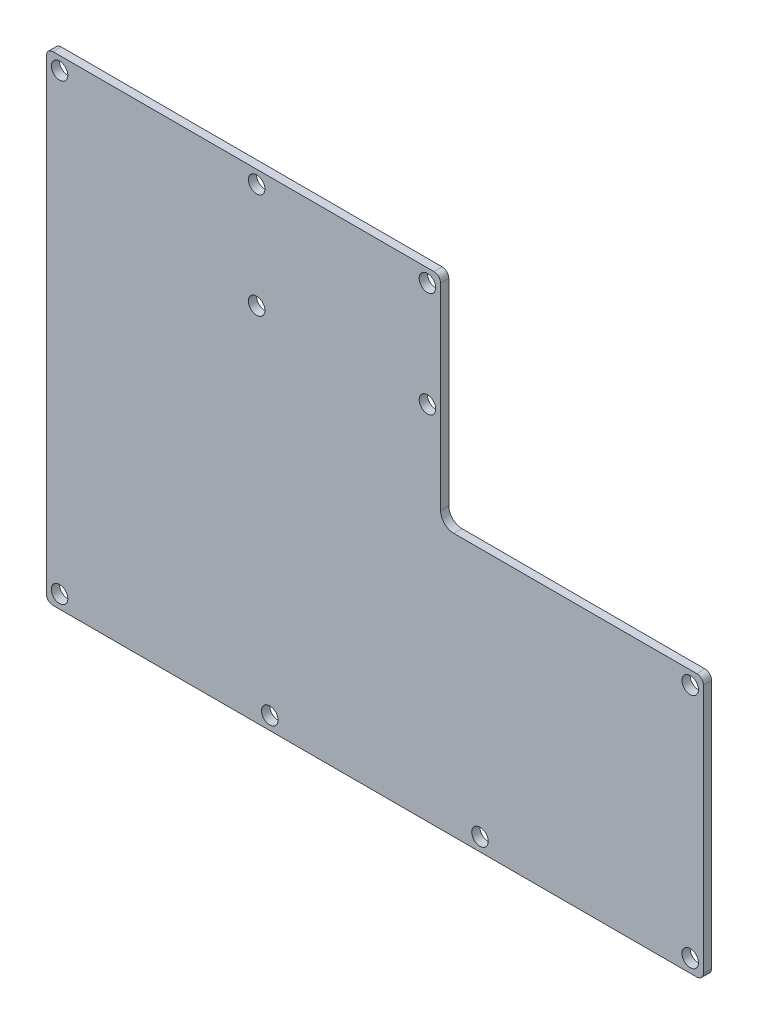
SolidWorks part; units mm, degrees
ref_plane "Front" through (0, 0, 0) normal (0, 0, 1) x (1, 0, 0)
ref_plane "Top" through (0, 0, 0) normal (0, 1, 0) x (1, 0, 0)
ref_plane "Right" through (0, 0, 0) normal (1, 0, 0) x (0, 0, -1)
sketch "Model" plane through (0, 0, 0) normal (0, 0, 1) x (1, 0, 0)
  line L0 (127, 49.53) -> (127, 1.27)
  line L1 (0, 91.44) -> (0, 1.27)
  line L2 (1.27, 0) -> (125.73, 0)
  line L3 (1.27, 92.71) -> (74.93, 92.71)
  line L4 (76.2, 91.44) -> (76.2, 53.34)
  line L5 (78.74, 50.8) -> (125.73, 50.8)
  arc A0 (125.73, 0) -> (127, 1.27) centre (125.73, 1.27) ccw
  arc A1 (0, 1.27) -> (1.27, 0) centre (1.27, 1.27) ccw
  arc A2 (76.2, 91.44) -> (74.93, 92.71) centre (74.93, 91.44) ccw
  arc A3 (1.27, 92.71) -> (0, 91.44) centre (1.27, 91.44) ccw
  arc A4 (76.2, 53.34) -> (78.74, 50.8) centre (78.74, 53.34) ccw
  arc A5 (127, 49.53) -> (125.73, 50.8) centre (125.73, 49.53) ccw
  circle A6 centre (2.54, 2.54) radius 1.6
  circle A7 centre (124.46, 2.54) radius 1.6
  circle A8 centre (2.54, 90.17) radius 1.6
  circle A9 centre (43.18, 2.54) radius 1.6
  circle A10 centre (83.82, 2.54) radius 1.6
  circle A11 centre (124.46, 48.26) radius 1.6
  circle A12 centre (73.66, 69.85) radius 1.6
  circle A13 centre (40.64, 69.85) radius 1.6
  circle A14 centre (40.64, 90.17) radius 1.6
  circle A15 centre (73.66, 90.17) radius 1.6
extrude "Boss-Extrude1" add sketch "Model" against normal blind 1.5875
